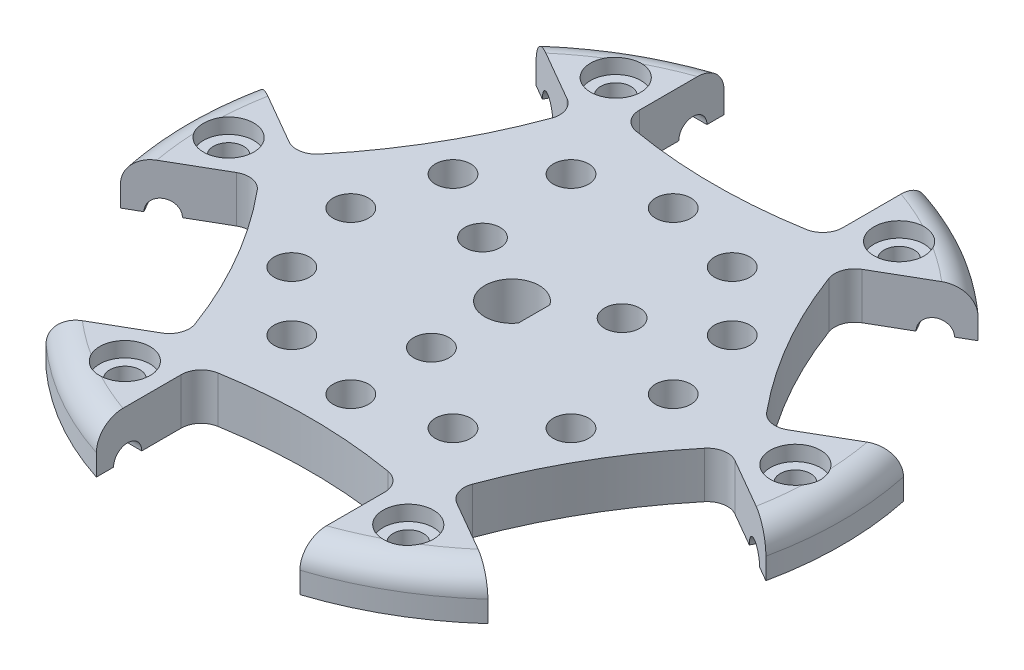
SolidWorks part; units mm, degrees
ref_plane "Plano frontal" through (0, 0, 0) normal (0, 0, 1) x (1, 0, 0)
ref_plane "Plano superior" through (0, 0, 0) normal (0, 1, 0) x (1, 0, 0)
ref_plane "Plano direito" through (0, 0, 0) normal (1, 0, 0) x (0, 0, -1)
sketch "Esboço1" plane through (0, 0, 0) normal (0, 0, 1) x (1, 0, 0)
  line L1 (-32.75, 2.1) -> (-32.75, 0)
  line L2 (-30.25, 4.6) -> (-6.07, 4.6)
  line L15 (-6.07, 4.6) -> (0, 4.6)
  line L17 (0, 0) -> (0, 4.6)
  line L18 (-32.75, 0) -> (0, 0)
  arc A3 (-30.25, 4.6) -> (-32.75, 2.1) centre (-30.25, 2.1) ccw
revolve "Revolução3" add sketch "Esboço1" angle 360 about L17
sketch "Esboço3" plane through (0, 0, 0) normal (0, -1, 0) x (1, 0, 0)
  line L2 (-10.1, 71.55) -> (10.1, 71.55)
  line L3 (-10.1, 71.55) -> (-10.1, 22.7384)
  line L4 (10.1, 71.55) -> (10.1, 22.7384)
  line L5 (10.1, -71.55) -> (-10.1, -71.55)
  line L6 (10.1, -71.55) -> (10.1, -22.7384)
  line L7 (-10.1, -71.55) -> (-10.1, -22.7384)
  line L10 (56.9141, 44.5219) -> (67.0141, 27.0281)
  line L11 (56.9141, 44.5219) -> (14.642, 20.116)
  line L12 (67.0141, 27.0281) -> (24.742, 2.6223)
  line L13 (-56.9141, -44.5219) -> (-67.0141, -27.0281)
  line L14 (-56.9141, -44.5219) -> (-14.642, -20.116)
  line L15 (-67.0141, -27.0281) -> (-24.742, -2.6223)
  line L18 (-67.0141, 27.0281) -> (-56.9141, 44.5219)
  line L19 (-67.0141, 27.0281) -> (-24.742, 2.6223)
  line L20 (-56.9141, 44.5219) -> (-14.642, 20.116)
  line L21 (67.0141, -27.0281) -> (56.9141, -44.5219)
  line L22 (67.0141, -27.0281) -> (24.742, -2.6223)
  line L23 (56.9141, -44.5219) -> (14.642, -20.116)
  arc A1 (-8.4375, 20.7671) -> (8.4375, 20.7671) centre (0, 70.05) ccw
  arc A2 (8.4375, 20.7671) -> (10.1, 22.7384) centre (8.1, 22.7384) ccw
  arc A3 (-8.4375, 20.7671) -> (-10.1, 22.7384) centre (-8.1, 22.7384) cw
  arc A4 (8.4375, -20.7671) -> (-8.4375, -20.7671) centre (0, -70.05) ccw
  arc A5 (-8.4375, -20.7671) -> (-10.1, -22.7384) centre (-8.1, -22.7384) ccw
  arc A6 (8.4375, -20.7671) -> (10.1, -22.7384) centre (8.1, -22.7384) cw
  arc A7 (13.766, 17.6906) -> (22.2035, 3.0764) centre (60.6651, 35.025) ccw
  arc A8 (22.2035, 3.0764) -> (24.742, 2.6223) centre (23.742, 4.3544) ccw
  arc A9 (13.766, 17.6906) -> (14.642, 20.116) centre (15.642, 18.384) cw
  arc A10 (-13.766, -17.6906) -> (-22.2035, -3.0764) centre (-60.6651, -35.025) ccw
  arc A11 (-22.2035, -3.0764) -> (-24.742, -2.6223) centre (-23.742, -4.3544) ccw
  arc A12 (-13.766, -17.6906) -> (-14.642, -20.116) centre (-15.642, -18.384) cw
  arc A13 (-22.2035, 3.0764) -> (-13.766, 17.6906) centre (-60.6651, 35.025) ccw
  arc A14 (-13.766, 17.6906) -> (-14.642, 20.116) centre (-15.642, 18.384) ccw
  arc A15 (-22.2035, 3.0764) -> (-24.742, 2.6223) centre (-23.742, 4.3544) cw
  arc A16 (22.2035, -3.0764) -> (13.766, -17.6906) centre (60.6651, -35.025) ccw
  arc A17 (13.766, -17.6906) -> (14.642, -20.116) centre (15.642, -18.384) ccw
  arc A18 (22.2035, -3.0764) -> (24.742, -2.6223) centre (23.742, -4.3544) cw
extrude "Corte-extrusão2" cut sketch "Esboço3" against normal blind 10
sketch "Esboço5" plane through (0, 0, 0) normal (0, -1, 0) x (1, 0, 0)
  line L0 (-12.6, 26.65) -> (12.6, 26.65)
  line L1 (-12.6, 28.05) -> (12.6, 28.05)
  line L10 (-12.6, 28.05) -> (-12.6, 26.65)
  line L13 (12.6, 28.05) -> (12.6, 26.65)
revolve "Corte-Revolução3" cut sketch "Esboço5" angle 360 about L1
sketch "Esboço6" plane through (0, 0, 0) normal (0, -1, 0) x (1, 0, 0)
  line L21 (-29.3796, 2.4131) -> (-16.7796, 24.2369)
  line L22 (-30.592, 3.1131) -> (-17.992, 24.9369)
  line L23 (-30.592, 3.1131) -> (-29.3796, 2.4131)
  line L24 (-17.992, 24.9369) -> (-16.7796, 24.2369)
revolve "Corte-Revolução4" cut sketch "Esboço6" angle 360 about L22
sketch "Esboço7" plane through (0, 0, 0) normal (0, -1, 0) x (1, 0, 0)
  line L9 (-16.7796, -24.2369) -> (-29.3796, -2.4131)
  line L10 (-17.992, -24.9369) -> (-30.592, -3.1131)
  line L11 (-17.992, -24.9369) -> (-16.7796, -24.2369)
  line L12 (-30.592, -3.1131) -> (-29.3796, -2.4131)
revolve "Corte-Revolução5" cut sketch "Esboço7" angle 360 about L10
sketch "Esboço8" plane through (0, 0, 0) normal (0, -1, 0) x (1, 0, 0)
  line L13 (16.7796, 24.2369) -> (29.3796, 2.4131)
  line L14 (17.992, 24.9369) -> (30.592, 3.1131)
  line L15 (17.992, 24.9369) -> (16.7796, 24.2369)
  line L16 (30.592, 3.1131) -> (29.3796, 2.4131)
revolve "Corte-Revolução6" cut sketch "Esboço8" angle 360 about L14
sketch "Esboço10" plane through (0, 0, 0) normal (0, -1, 0) x (1, 0, 0)
  line L1 (12.6, -26.65) -> (-12.6, -26.65)
  line L2 (12.6, -28.05) -> (-12.6, -28.05)
  line L3 (12.6, -28.05) -> (12.6, -26.65)
  line L4 (-12.6, -28.05) -> (-12.6, -26.65)
revolve "Corte-Revolução7" cut sketch "Esboço10" angle 360 about L2
sketch "Esboço11" plane through (0, 0, 0) normal (0, -1, 0) x (1, 0, 0)
  line L5 (29.3796, -2.4131) -> (16.7796, -24.2369)
  line L6 (30.592, -3.1131) -> (17.992, -24.9369)
  line L7 (30.592, -3.1131) -> (29.3796, -2.4131)
  line L8 (17.992, -24.9369) -> (16.7796, -24.2369)
revolve "Corte-Revolução8" cut sketch "Esboço11" angle 360 about L6
sketch "Esboço12" plane through (0, 0, 0) normal (0, -1, 0) x (1, 0, 0)
  circle A1 centre (0, 16) radius 1.75
  circle A2 centre (-8, 13.8564) radius 1.75
  circle A3 centre (-13.8564, 8) radius 1.75
  circle A4 centre (-16, 0) radius 1.75
  circle A5 centre (-13.8564, -8) radius 1.75
  circle A6 centre (-8, -13.8564) radius 1.75
  circle A7 centre (0, -16) radius 1.75
  circle A8 centre (8, -13.8564) radius 1.75
  circle A9 centre (13.8564, -8) radius 1.75
  circle A10 centre (16, 0) radius 1.75
  circle A11 centre (13.8564, 8) radius 1.75
  circle A12 centre (8, 13.8564) radius 1.75
  circle A13 centre (28.1296, 0) radius 1.3
  circle A14 centre (14.0648, 24.3609) radius 1.3
  circle A15 centre (-14.0648, 24.3609) radius 1.3
  circle A16 centre (-28.1296, 0) radius 1.3
  circle A18 centre (14.0648, -24.3609) radius 1.3
  circle A19 centre (-14.0648, -24.3609) radius 1.3
  circle A22 centre (0, 8) radius 1.75
  circle A23 centre (-6.9282, -4) radius 1.75
  circle A24 centre (6.9282, -4) radius 1.75
extrude "Corte-extrusão4" cut sketch "Esboço12" against normal through all
sketch "Esboço13" plane through (0, 4.6, 0) normal (0, 1, 0) x (1, 0, 0)
  circle A0 centre (-14.0648, 24.3609) radius 2.05
  circle A1 centre (-28.1296, 0) radius 2.05
  circle A2 centre (-14.0648, -24.3609) radius 2.05
  circle A3 centre (14.0648, -24.3609) radius 2.05
  circle A4 centre (28.1296, 0) radius 2.04
  circle A5 centre (14.0648, 24.3609) radius 2.04
extrude "Corte-extrusão5" cut sketch "Esboço13" against normal blind 1.5
sketch "Esboço14" plane through (0, 0, 0) normal (0, -1, 0) x (1, 0, 0)
  line L2 (2.1, 1.533) -> (2.1, -1.533)
  arc A0 (2.1, 1.533) -> (2.1, -1.533) centre (0, 0) ccw
extrude "Corte-extrusão6" cut sketch "Esboço14" against normal through all
sketch "Esboço15" plane through (0, 4.6, 0) normal (0, 1, 0) x (1, 0, 0)
  circle A0 centre (-14.0648, 24.3609) radius 1.5
  circle A1 centre (14.0648, 24.3609) radius 1.5
  circle A2 centre (-14.0648, -24.3609) radius 1.5
  circle A3 centre (14.0648, -24.3609) radius 1.5
  circle A4 centre (-28.1296, 0) radius 1.5
  circle A5 centre (28.1296, 0) radius 1.5
extrude "Corte-extrusão7" cut sketch "Esboço15" against normal through all
sketch "Esboço16" plane through (0, 4.6, 0) normal (0, 1, 0) x (1, 0, 0)
  circle A0 centre (-14.0648, 24.3609) radius 2.5
  circle A1 centre (14.0648, 24.3609) radius 2.5
  circle A2 centre (-14.0648, -24.3609) radius 2.5
  circle A3 centre (14.0648, -24.3609) radius 2.5
  circle A4 centre (28.1296, 0) radius 2.5
  circle A5 centre (-28.1296, 0) radius 2.5
extrude "Corte-extrusão8" cut sketch "Esboço16" against normal blind 1.5
sketch "Esboço18" plane through (0, 4.6, 0) normal (0, 1, 0) x (1, 0, 0)
  line L2 (2.2, -1.5652) -> (2.2, 1.5652)
  arc A0 (2.2, 1.5652) -> (2.2, -1.5652) centre (0, 0) ccw
extrude "Corte-extrusão9" cut sketch "Esboço18" against normal through all
